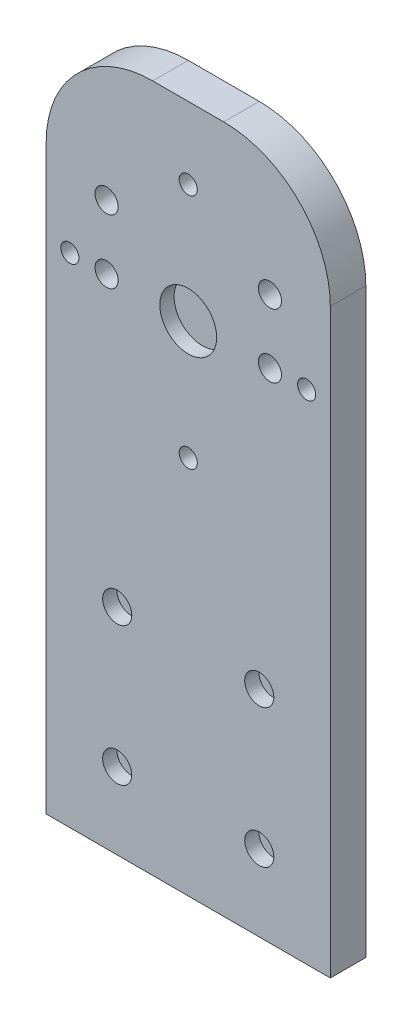
SolidWorks part; units mm, degrees
ref_plane "Front Plane" through (0, 0, 0) normal (0, 0, 1) x (1, 0, 0)
ref_plane "Top Plane" through (0, 0, 0) normal (0, 1, 0) x (1, 0, 0)
ref_plane "Right Plane" through (0, 0, 0) normal (1, 0, 0) x (0, 0, -1)
sketch "Sketch1" plane through (0, 0, 0) normal (0, 0, 1) x (1, 0, 0)
  line L1 (1820.4212, -1907.5842) -> (1740.4212, -1907.5842)
  line L2 (1820.4212, -1907.5842) -> (1820.4212, -1713.8282)
  line L3 (1820.4212, -1713.8282) -> (1740.4212, -1713.8282)
  line L4 (1740.4212, -1907.5842) -> (1740.4212, -1713.8282)
  line L5 (1764.2212, -1739.2194) -> (1755.2212, -1739.2194) construction
extrude "Boss-Extrude1" add sketch "Sketch1" along normal blind 10
sketch "Schizzo2" plane through (0, 0, 10) normal (0, 0, 1) x (1, 0, 0)
  circle A0 centre (1747.0882, -1767.4194) radius 2.55 construction
  circle A1 centre (1747.0882, -1767.4194) radius 2.55
  circle A2 centre (1780.4212, -1734.0864) radius 2.55 construction
  circle A3 centre (1780.4212, -1734.0864) radius 2.55
  circle A4 centre (1813.7542, -1767.4194) radius 2.55 construction
  circle A5 centre (1813.7542, -1767.4194) radius 2.55
  circle A6 centre (1780.4212, -1800.7524) radius 2.55 construction
  circle A7 centre (1780.4212, -1800.7524) radius 2.55
extrude "Taglio-Estrusione4" cut sketch "Schizzo2" against normal through all
sketch "Schizzo3" plane through (0, 0, 10) normal (0, 0, 1) x (1, 0, 0)
  circle A0 centre (1757.4212, -1749.4194) radius 3.25 construction
  circle A1 centre (1803.4212, -1749.4194) radius 3.25 construction
  circle A2 centre (1757.4212, -1767.4194) radius 3.25 construction
  circle A3 centre (1803.4212, -1767.4194) radius 3.25 construction
  circle A4 centre (1757.4212, -1749.4194) radius 3.25
  circle A5 centre (1803.4212, -1749.4194) radius 3.25
  circle A6 centre (1757.4212, -1767.4194) radius 3.25
  circle A7 centre (1803.4212, -1767.4194) radius 3.25
extrude "Taglio-Estrusione5" cut sketch "Schizzo3" against normal through all contours A5 | A7 | A4 | A6
sketch "Schizzo6" plane through (0, 0, 10) normal (0, 0, 1) x (1, 0, 0)
  line L0 (1756.3212, -1839.4194) -> (1756.3212, -3739.4194) construction
  line L1 (1764.5212, -1839.4194) -> (1764.5212, -3739.4194) construction
  line L2 (1796.3212, -1839.4194) -> (1796.3212, -3739.4194) construction
  line L3 (1804.5212, -1839.4194) -> (1804.5212, -3739.4194) construction
  line L4 (1756.3212, -1839.4194) -> (1756.3212, -3739.4194) construction
  line L5 (1764.5212, -1839.4194) -> (1764.5212, -3739.4194) construction
  line L6 (1796.3212, -1839.4194) -> (1796.3212, -3739.4194) construction
  line L7 (1804.5212, -1839.4194) -> (1804.5212, -3739.4194) construction
  line L10 (1756.3212, -1866.5935) -> (1804.5212, -1866.5935) construction
  circle A0 centre (1760.4212, -1847.1168) radius 4.1
  circle A1 centre (1800.4212, -1847.1168) radius 4.1
  circle A2 centre (1800.4212, -1886.0703) radius 4.1
  circle A3 centre (1760.4212, -1886.0703) radius 4.1
extrude "Taglio-Estrusione6" cut sketch "Schizzo6" against normal blind 4
fillet "Raccordo1" radius 30 2 edges at (1820.4212, -1713.8282, 5) (1740.4212, -1713.8282, 5)
sketch "Schizzo7" plane through (0, 0, 10) normal (0, 0, 1) x (1, 0, 0)
  circle A0 centre (1780.4212, -1767.4194) radius 6 construction
  circle A1 centre (1780.4212, -1767.4194) radius 6 construction
  arc A2 (1767.1345, -1753.7678) -> (1768.0203, -1752.9584) centre (1780.4212, -1767.4194) ccw construction
  arc A3 (1767.1345, -1753.7678) -> (1768.0203, -1752.9584) centre (1780.4212, -1767.4194) ccw construction
  circle A4 centre (1780.4212, -1767.4194) radius 8
  dimension "D1" = 16
extrude "Taglio-Estrusione7" cut sketch "Schizzo7" against normal blind 4
